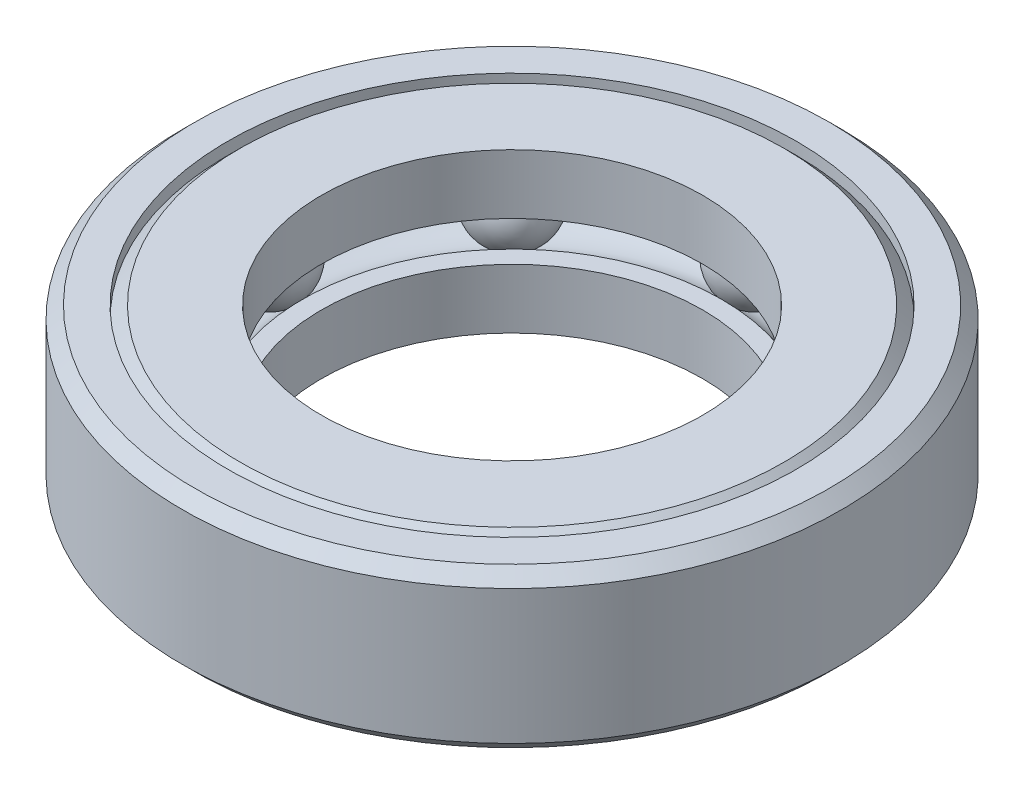
SolidWorks part; units mm, degrees
ref_plane "Front Plane" through (0, 0, 0) normal (0, 0, 1) x (1, 0, 0)
ref_plane "Top Plane" through (0, 0, 0) normal (0, 1, 0) x (1, 0, 0)
ref_plane "Right Plane" through (0, 0, 0) normal (1, 0, 0) x (0, 0, -1)
sketch "Sketch1" plane through (0, 0, 0) normal (1, 0, 0) x (0, 0, -1)
  line L0 (32.9406, 0) -> (-32.9406, 0) construction
  line L1 (0, -7.9375) -> (0, 7.9375) construction
  line L2 (-19.05, 1.9844) -> (-19.05, 7.9375) construction
  line L3 (-29.6466, 0) -> (-28.317, 0) construction
  line L4 (-20.3795, 0) -> (-19.05, 0) construction
  line L5 (-24.3483, 0) -> (-24.3483, 3.9688) construction
  line L6 (-19.05, 1.9844) -> (-20.9112, 1.9844) construction
  line L7 (-27.7853, 1.9844) -> (-29.6466, 1.9844) construction
  line L8 (-29.6466, 1.9844) -> (-29.6466, 5.4716) construction
  line L9 (-29.6466, 5.4716) -> (-27.1807, 7.9375) construction
  line L10 (-27.1807, 7.9375) -> (-19.05, 7.9375) construction
  line L11 (-27.1807, -7.9375) -> (-19.05, -7.9375) construction
  line L12 (-29.6466, -5.4716) -> (-27.1807, -7.9375) construction
  line L13 (-29.6466, -1.9844) -> (-29.6466, -5.4716) construction
  line L14 (-27.7853, -1.9844) -> (-29.6466, -1.9844) construction
  line L15 (-19.05, -1.9844) -> (-20.9112, -1.9844) construction
  line L16 (-19.05, -1.9844) -> (-19.05, -7.9375) construction
  line L17 (-19.05, 7.9375) -> (-19.05, -7.9375)
  line L18 (19.05, 7.9375) -> (19.05, -7.9375)
  line L19 (-27.1807, 7.9375) -> (27.1807, 7.9375) construction
  line L20 (-27.1807, -7.9375) -> (27.1807, -7.9375) construction
  circle A0 centre (-24.3483, 0) radius 3.9688 construction
  point P0 (-19.05, 0)
  point P4 (0, 0)
  point P8 (0, 0)
  point P14 (-29.6466, 0)
  point P18 (-24.3483, 1.9844)
  point P23 (-24.3483, -1.9844)
  point P35 (-19.05, 0)
  dimension "D1" = 7.9375
  dimension "OD" = 65.8813
  dimension "ID" = 38.1
  dimension "D2" = 59.2931
  dimension "D3" = 45
  dimension "Thickness" = 15.875
sketch "Sketch2" plane through (0, 0, 0) normal (1, 0, 0) x (0, 0, -1)
  line L0 (-27.7853, 1.9844) -> (-29.6466, 1.9844)
  line L1 (-29.6466, 1.9844) -> (-29.6466, 5.4716)
  line L2 (-29.6466, 5.4716) -> (-27.1807, 7.9375)
  line L3 (-27.1807, 7.9375) -> (-19.05, 7.9375)
  line L4 (-19.05, 7.9375) -> (-19.05, 1.9844)
  line L5 (-19.05, 1.9844) -> (-20.9112, 1.9844)
  line L6 (32.9406, 0) -> (-32.9406, 0) construction
  line L7 (32.9406, 0) -> (-32.9406, 0) construction
  line L8 (-19.05, -1.9844) -> (-20.9112, -1.9844)
  line L9 (-19.05, -7.9375) -> (-19.05, -1.9844)
  line L10 (-27.1807, -7.9375) -> (-19.05, -7.9375)
  line L11 (-29.6466, -5.4716) -> (-27.1807, -7.9375)
  line L12 (-29.6466, -1.9844) -> (-29.6466, -5.4716)
  line L13 (-27.7853, -1.9844) -> (-29.6466, -1.9844)
  arc A0 (-27.7853, 1.9844) -> (-20.9112, 1.9844) centre (-24.3483, 0) cw
  circle A1 centre (-24.3483, 0) radius 3.9688 construction
  arc A2 (-27.7853, -1.9844) -> (-20.9112, -1.9844) centre (-24.3483, 0) ccw
revolve "Revolve1" add sketch "Sketch2" angle 360 about L1
sketch "Sketch3" plane through (0, 0, 0) normal (1, 0, 0) x (0, 0, -1)
  line L0 (-28.4136, 6.7046) -> (-28.4136, 7.9375)
  line L1 (-29.6466, 5.4716) -> (-27.1807, 7.9375) construction
  line L2 (-32.9406, 6.7046) -> (-31.7077, 7.9375)
  line L3 (-32.9406, 6.7046) -> (-32.9406, -6.7046)
  line L4 (-31.7077, 7.9375) -> (-28.4136, 7.9375)
  line L5 (-27.1807, 7.9375) -> (-19.05, 7.9375) construction
  line L6 (32.9406, 0) -> (-32.9406, 0) construction
  line L7 (32.9406, 0) -> (-32.9406, 0) construction
  line L8 (-31.7077, -7.9375) -> (-28.4136, -7.9375)
  line L9 (-32.9406, -6.7046) -> (-31.7077, -7.9375)
  line L10 (-28.4136, -6.7046) -> (-28.4136, -7.9375)
  line L11 (-28.4136, 6.7046) -> (-29.6466, 5.4716)
  line L12 (-29.6466, 5.4716) -> (-29.6466, -5.4716)
  line L13 (-29.6466, -5.4716) -> (-28.4136, -6.7046)
revolve "Revolve2" add sketch "Sketch3" angle 360 about L1
sketch "Sketch4" plane through (0, 0, 0) normal (1, 0, 0) x (0, 0, -1)
  line L0 (-24.3483, 3.9688) -> (-24.3483, -3.9688)
  circle A0 centre (-24.3483, 0) radius 3.9688 construction
  arc A1 (-24.3483, -3.9688) -> (-24.3483, 3.9688) centre (-24.3483, 0) ccw
revolve "Revolve3" add sketch "Sketch4" angle 360 about L0
pattern_circular "CirPattern1" count 8 over 360 about axis through (0, 0, 0) along (0, 1, 0) of bodies 107
sketch "Sketch5" plane through (0, 0, 0) normal (1, 0, 0) x (0, 0, -1)
  line L0 (-20.9112, 1.9844) -> (-19.05, 1.9844)
  line L1 (19.05, 1.9844) -> (20.9112, 1.9844)
  line L2 (-19.05, 1.9844) -> (-19.05, 7.9375)
  line L3 (19.05, 7.9375) -> (19.05, 1.9844)
  line L4 (27.1807, 7.9375) -> (19.05, 7.9375)
  line L5 (-19.05, 7.9375) -> (-27.1807, 7.9375)
  line L6 (-27.1807, 7.9375) -> (-29.6466, 5.4716)
  line L7 (29.6466, 5.4716) -> (27.1807, 7.9375)
  line L8 (-29.6466, 5.4716) -> (-29.6466, 1.9844)
  line L9 (29.6466, 1.9844) -> (29.6466, 5.4716)
  line L10 (-29.6466, 1.9844) -> (-27.7853, 1.9844)
  line L11 (27.7853, 1.9844) -> (29.6466, 1.9844)
  line L12 (27.7853, 1.9844) -> (29.6466, 1.9844)
  line L13 (-29.6466, 1.9844) -> (-27.7853, 1.9844)
  line L14 (29.6466, 1.9844) -> (29.6466, 5.4716)
  line L15 (-29.6466, 5.4716) -> (-29.6466, 1.9844)
  line L16 (29.6466, 5.4716) -> (27.1807, 7.9375)
  line L17 (-27.1807, 7.9375) -> (-29.6466, 5.4716)
  line L18 (-19.05, 7.9375) -> (-27.1807, 7.9375)
  line L19 (27.1807, 7.9375) -> (19.05, 7.9375)
  line L20 (19.05, 7.9375) -> (19.05, 1.9844)
  line L21 (-19.05, 1.9844) -> (-19.05, 7.9375)
  line L22 (19.05, 1.9844) -> (20.9112, 1.9844)
  line L23 (-20.9112, 1.9844) -> (-19.05, 1.9844)
  line L24 (20.9112, -1.9844) -> (19.05, -1.9844)
  line L25 (-19.05, -1.9844) -> (-20.9112, -1.9844)
  line L26 (-19.05, -7.9375) -> (-19.05, -1.9844)
  line L27 (19.05, -1.9844) -> (19.05, -7.9375)
  line L28 (-27.1807, -7.9375) -> (-19.05, -7.9375)
  line L29 (19.05, -7.9375) -> (27.1807, -7.9375)
  line L30 (27.1807, -7.9375) -> (29.6466, -5.4716)
  line L31 (-29.6466, -5.4716) -> (-27.1807, -7.9375)
  line L32 (-29.6466, -1.9844) -> (-29.6466, -5.4716)
  line L33 (29.6466, -5.4716) -> (29.6466, -1.9844)
  line L34 (29.6466, -1.9844) -> (27.7853, -1.9844)
  line L35 (-27.7853, -1.9844) -> (-29.6466, -1.9844)
  line L36 (-27.7853, -1.9844) -> (-29.6466, -1.9844)
  line L37 (29.6466, -1.9844) -> (27.7853, -1.9844)
  line L38 (29.6466, -5.4716) -> (29.6466, -1.9844)
  line L39 (-29.6466, -1.9844) -> (-29.6466, -5.4716)
  line L40 (-29.6466, -5.4716) -> (-27.1807, -7.9375)
  line L41 (27.1807, -7.9375) -> (29.6466, -5.4716)
  line L42 (19.05, -7.9375) -> (27.1807, -7.9375)
  line L43 (-27.1807, -7.9375) -> (-19.05, -7.9375)
  line L44 (19.05, -1.9844) -> (19.05, -7.9375)
  line L45 (-19.05, -7.9375) -> (-19.05, -1.9844)
  line L46 (-19.05, -1.9844) -> (-20.9112, -1.9844)
  line L47 (20.9112, -1.9844) -> (19.05, -1.9844)
  line L48 (-29.6466, -5.4716) -> (-29.6466, 5.4716)
  line L49 (29.6466, 5.4716) -> (29.6466, -5.4716)
  line L50 (29.6466, -5.4716) -> (28.4136, -6.7046)
  line L51 (-28.4136, -6.7046) -> (-29.6466, -5.4716)
  line L52 (-12.8207, -7.1438) -> (-28.4136, -6.7046)
  line L53 (28.4136, -6.7046) -> (12.8207, -7.1438)
  line L54 (-14.3685, -7.1438) -> (-12.8207, -7.1438)
  line L55 (12.8207, -7.1438) -> (14.3685, -7.1438)
  line L56 (14.3685, -7.1438) -> (15.4781, -6.0341)
  line L57 (-15.4781, -6.0341) -> (-14.3685, -7.1438)
  line L58 (-15.4781, 6.0341) -> (-15.4781, -6.0341)
  line L59 (15.4781, -6.0341) -> (15.4781, 6.0341)
  line L60 (-14.3685, 7.1438) -> (-15.4781, 6.0341)
  line L61 (15.4781, 6.0341) -> (31.7077, 7.9375)
  line L62 (31.7077, 7.9375) -> (28.4136, 7.9375)
  line L63 (-12.8207, 7.1438) -> (-14.3685, 7.1438)
  line L64 (-28.4136, 6.7046) -> (-12.8207, 7.1438)
  line L65 (28.4136, 7.9375) -> (28.4136, 6.7046)
  line L66 (-29.6466, 5.4716) -> (-28.4136, 6.7046)
  line L67 (28.4136, 6.7046) -> (29.6466, 5.4716)
  line L68 (28.4136, 6.7046) -> (29.6466, 5.4716)
  line L69 (-29.6466, 5.4716) -> (-28.4136, 6.7046)
  line L73 (31.7077, 7.9375) -> (28.4136, 7.9375)
  line L84 (-28.4136, -6.7046) -> (-29.6466, -5.4716)
  line L85 (29.6466, -5.4716) -> (28.4136, -6.7046)
  line L86 (29.6466, 5.4716) -> (29.6466, -5.4716)
  line L87 (-29.6466, -5.4716) -> (-29.6466, 5.4716)
  line L88 (-19.05, 7.9375) -> (19.05, 7.9375)
  line L89 (-19.05, 1.9844) -> (19.05, 1.9844)
  line L90 (19.05, -1.9844) -> (-19.05, -1.9844)
  line L91 (-19.05, -7.9375) -> (19.05, -7.9375)
  arc A0 (-20.9112, 1.9844) -> (-27.7853, 1.9844) centre (-24.3483, 0) ccw
  arc A1 (27.7853, 1.9844) -> (20.9112, 1.9844) centre (24.3483, 0) ccw
  arc A2 (27.7853, 1.9844) -> (20.9112, 1.9844) centre (24.3483, 0) ccw
  arc A3 (-20.9112, 1.9844) -> (-27.7853, 1.9844) centre (-24.3483, 0) ccw
  arc A4 (-27.7853, -1.9844) -> (-20.9112, -1.9844) centre (-24.3483, 0) ccw
  arc A5 (20.9112, -1.9844) -> (27.7853, -1.9844) centre (24.3483, 0) ccw
  arc A6 (20.9112, -1.9844) -> (27.7853, -1.9844) centre (24.3483, 0) ccw
  arc A7 (-27.7853, -1.9844) -> (-20.9112, -1.9844) centre (-24.3483, 0) ccw
  circle A9 centre (24.3483, 0) radius 3.9688
  circle A10 centre (-24.3483, 0) radius 3.9688
  circle A11 centre (-24.3483, 0) radius 3.9688
sketch "Sketch6" plane through (0, 0, 0) normal (0, 1, 0) x (1, 0, 0)
  circle A0 centre (0, 0) radius 32.9406
  circle A1 centre (0, 0) radius 19.05
  dimension "OD Toleranced" = 65.8813
  dimension "For Shaft Diameter for Drawing" = 38.1
equation "\"D1@Sketch1\"=\"Thickness@Sketch1\"/2"
equation "\"D2@Sketch1\"=\"OD@Sketch1\"*.9"
equation "\"D1@CirPattern1\"=\"OD@Sketch1\"*3"
